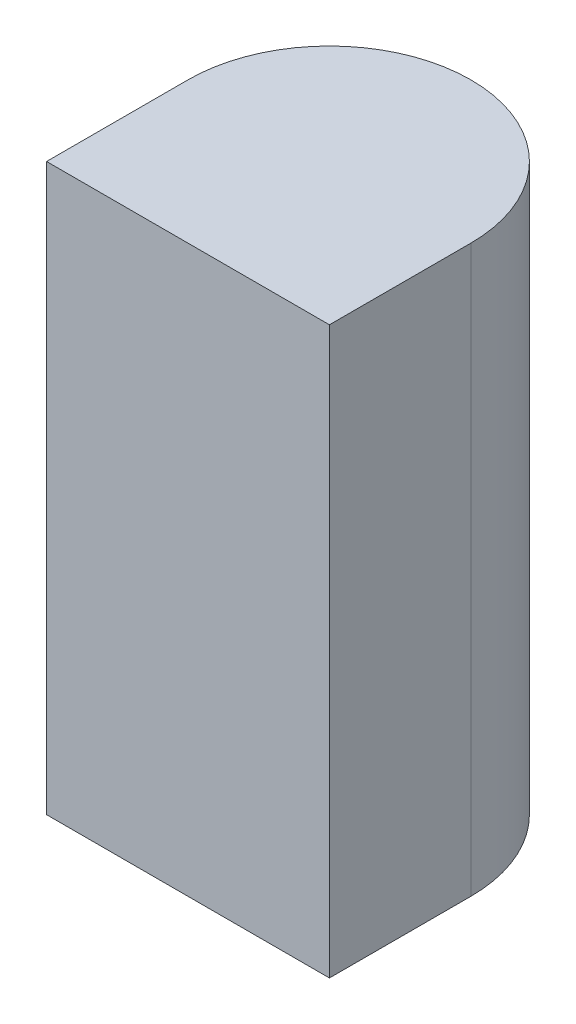
SolidWorks part; units mm, degrees
ref_plane "Přední rovina" through (0, 0, 0) normal (0, 0, 1) x (1, 0, 0)
ref_plane "Horní rovina" through (0, 0, 0) normal (0, 1, 0) x (1, 0, 0)
ref_plane "Pravá rovina" through (0, 0, 0) normal (1, 0, 0) x (0, 0, -1)
sketch "Sketch1" plane through (0, 0, 0) normal (0, 1, 0) x (1, 0, 0)
  line L1 (-5, -10) -> (5, -10)
  line L2 (-5, -10) -> (-5, -5)
  line L4 (5, -10) -> (5, -5)
  arc A0 (-5, -5) -> (5, -5) centre (0, -5) cw
  dimension "D1" = 10
  dimension "D2" = 5
extrude "Boss-Extrude1" add sketch "Sketch1" along normal blind 20
equation "\"R\" = 5'Radius"
equation "\"D1@Sketch1\"=\"R\"*2"
equation "\"D2@Sketch1\"=\"R\""
equation "\"H\"= 20'Extrude height"
equation "\"D1@Boss-Extrude1\"=\"H\""
